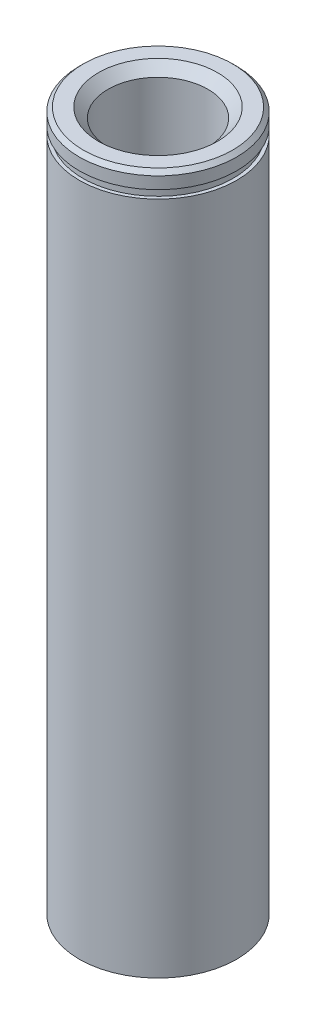
SolidWorks part; units mm, degrees
material "6061-T6 (SS)"
ref_plane "Front Plane" through (0, 0, 0) normal (0, 0, 1) x (1, 0, 0)
ref_plane "Top Plane" through (0, 0, 0) normal (0, 1, 0) x (1, 0, 0)
ref_plane "Right Plane" through (0, 0, 0) normal (1, 0, 0) x (0, 0, -1)
sketch "Sketch1" plane through (0, 0, 0) normal (1, 0, 0) x (0, 0, -1)
  line L0 (0, 0) -> (0, 10.2143) construction
  line L1 (12.5, 108.4372) -> (11.95, 108.4372)
  line L2 (6.35, 0) -> (12.5, 0)
  line L3 (6.35, 0) -> (6.35, 110.9772)
  line L4 (6.35, 110.9772) -> (12.5, 110.9772)
  line L5 (12.5, 0) -> (12.5, 107.1372)
  line L6 (11.95, 108.4372) -> (11.95, 107.1372)
  line L7 (11.95, 107.1372) -> (12.5, 107.1372)
  line L8 (12.5, 108.4372) -> (12.5, 110.9772)
  dimension "D1" = 12.7
  dimension "D2" = 25
  dimension "D3" = 107.1372
  dimension "D4" = 2.54
  dimension "D5" = 23.9
  dimension "D6" = 1.3
revolve "Revolve1" add sketch "Sketch1" angle 360 about L0
hole_wizard "5/8 (0.625) Diameter Hole1" positions "Sketch2" profile "Sketch4" hole size "5/8" standard "ANSI Inch"
sketch "Sketch2" plane through (0, 110.9772, 0) normal (0, 1, 0) x (1, 0, 0)
  point P0 (0, 0)
sketch "Sketch4" plane through (0, 110.9772, 0) normal (1, 0, 0) x (0, 0, 1)
  line L0 (0, 0) -> (0, 74.6193)
  line L1 (0, 74.6193) -> (7.9375, 69.85)
  line L2 (7.9375, 69.85) -> (7.9375, 0)
  line L5 (7.9375, 0) -> (0, 0)
  line L10 (0, 74.6193) -> (-7.9375, 69.85) construction
  line L11 (0, -6.35) -> (0, 107.95) construction
  dimension "Hole Dia." = 15.875
  dimension "Hole Depth" = 69.85
  dimension "Drill Angle" = 118
chamfer "Chamfer1" distance 0.635 angle 45 1 edges at (0, 110.9772, -12.5)
hole_wizard "#8-32 Tapped Hole1" positions "Sketch6" profile "Sketch7" tap size "#8-32" standard "ANSI Inch"
sketch "Sketch6" plane through (0, 0, 0) normal (0, -1, 0) x (-1, 0, 0)
  line L0 (0, -12.5) -> (0, -6.35) construction
  line L1 (0, 6.35) -> (0, 12.5) construction
  circle A0 centre (0, 0) radius 12.5 construction
  circle A1 centre (0, 0) radius 6.35 construction
  point P10 (0, -9.425)
  point P17 (-9.425, 0)
  point P18 (0, 9.425)
  point P19 (9.425, 0)
  dimension "D1" = 4
sketch "Sketch7" plane through (-9.425, 0, 0) normal (1, 0, 0) x (0, 0, -1)
  line L0 (0, 0) -> (0, 13.7378)
  line L1 (0, 13.7378) -> (1.7272, 12.7)
  line L2 (1.7272, 12.7) -> (1.7272, 0)
  line L5 (1.7272, 0) -> (0, 0)
  line L10 (0, 13.7378) -> (-1.7272, 12.7) construction
  line L11 (0, -6.35) -> (0, 107.95) construction
  dimension "Tap Drill Dia." = 3.4544
  dimension "Tap Drill Depth" = 12.7
  dimension "Drill Angle" = 118
cosmetic thread "Hole Thread1" parameters "D1"=8.3312, "D2"=4.1656
cosmetic thread "Hole Thread2" parameters "D1"=8.3312, "D2"=4.1656
cosmetic thread "Hole Thread3" parameters "D1"=8.3312, "D2"=4.1656
cosmetic thread "Hole Thread4" parameters "D1"=8.3312, "D2"=4.1656
sketch "Sketch8" plane through (0, 0, 0) normal (0, -1, 0) x (1, 0, 0)
  line L0 (0, 0) -> (6.35, 0) construction
  line L1 (0, 0) -> (4.4901, 4.4901) construction
  line L2 (4.4901, 4.4901) -> (8.8388, 8.8388) construction
  circle A0 centre (0, 0) radius 6.35 construction
  circle A2 centre (6.6645, 6.6645) radius 2.3685
  circle A3 centre (6.6645, -6.6645) radius 2.3685
  circle A4 centre (-6.6645, -6.6645) radius 2.3686
  circle A5 centre (-6.6645, 6.6645) radius 2.3686
  circle A6 centre (0, 0) radius 9.425 construction
  circle A7 centre (0, 0) radius 12.5 construction
  point P9 (6.6645, 6.6645)
  point P20 (0, 0)
  dimension "D2" = 4.7371
  dimension "D1" = 45
  dimension "D3" = 4
extrude "Cut-Extrude1" cut sketch "Sketch8" against normal blind 12.7
sketch "Sketch9" plane through (0, 0, 0) normal (0, 0, 1) x (1, 0, 0)
  line L0 (0, 108.4372) -> (0, 110.9772) construction
  line L1 (-11.95, 108.4372) -> (11.95, 108.4372) construction
  line L2 (7.9375, 110.9772) -> (-7.9375, 110.9772) construction
  circle A0 centre (0, 109.7072) radius 1.5875
  dimension "D1" = 3.175
extrude "Cut-Extrude2" [suppressed] cut sketch "Sketch9" along normal up to next
chamfer "Chamfer2" distance 1.524 angle 45 1 edges at (0, 110.9772, 7.9375)
equation "\"D6@Sketch1\"=1.3mm"
equation "\"D5@Sketch1\"=23.9mm"
equation "\"D2@Sketch1\"=25mm"
